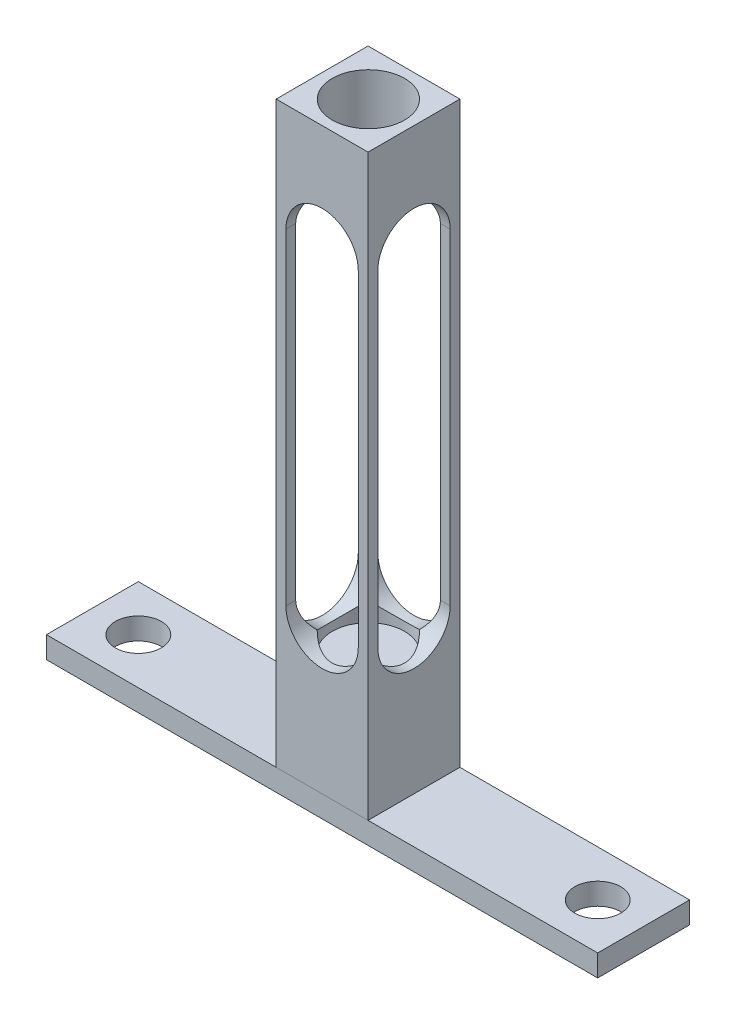
SolidWorks part; units mm, degrees
ref_plane "Front" through (0, 0, 0) normal (0, 0, 1) x (1, 0, 0)
ref_plane "Top" through (0, 0, 0) normal (0, 1, 0) x (1, 0, 0)
ref_plane "Right" through (0, 0, 0) normal (1, 0, 0) x (0, 0, -1)
other "Center of Mass"
sketch "Sketch1" plane through (0, 0, 0) normal (0, 0, 1) x (1, 0, 0)
  line L1 (0, 0) -> (12.7, 0)
  line L2 (0, 0) -> (0, 80)
  line L3 (0, 80) -> (12.7, 80)
  line L4 (12.7, 0) -> (12.7, 80)
  dimension "D1" = 80
  dimension "D2" = 12.7
extrude "Boss-Extrude1" add sketch "Sketch1" along normal blind 12.7
ref_point "Point1"
sketch "Sketch4" plane through (0, 0, 0) normal (0, -1, 0) x (-1, 0, 0)
  line L1 (31.7572, 0.0012) -> (-44.4428, 0.0012)
  line L2 (31.7572, 0.0012) -> (31.7572, -12.6988)
  line L3 (31.7572, -12.6988) -> (-44.4428, -12.6988)
  line L4 (-44.4428, 0.0012) -> (-44.4428, -12.6988)
  line L5 (31.7572, 0.0012) -> (-44.4428, -12.6988) construction
  line L6 (31.7572, -12.6988) -> (-44.4428, 0.0012) construction
  point P0 (-6.3428, -6.3488)
  dimension "D1" = 12.7
  dimension "D2" = 76.2
extrude "Boss-Extrude3" add sketch "Sketch4" along normal blind 3
sketch "Sketch12" plane through (0, 0, 12.7) normal (0, 0, 1) x (1, 0, 0)
  line L0 (6.35, 20) -> (6.35, 65.1) construction
  line L1 (1.35, 20) -> (1.35, 65.1)
  line L2 (11.35, 20) -> (11.35, 65.1)
  line L3 (44.4428, -3) -> (-31.7572, -3) construction
  line L4 (12.7, 0) -> (12.7, 80) construction
  arc A0 (1.35, 20) -> (11.35, 20) centre (6.35, 20) ccw
  arc A1 (11.35, 65.1) -> (1.35, 65.1) centre (6.35, 65.1) ccw
  point P2 (6.35, 42.55)
  dimension "D1" = 23
  dimension "D2" = 6.35
extrude "Cut-Extrude5" cut sketch "Sketch12" against normal blind 23
sketch "Sketch13" plane through (12.7, 0, 0) normal (1, 0, 0) x (0, 0, -1)
  line L0 (-6.35, 20) -> (-6.35, 65.1) construction
  line L1 (-11.35, 20) -> (-11.35, 65.1)
  line L2 (-1.35, 20) -> (-1.35, 65.1)
  line L3 (0.0012, -3) -> (-12.6988, -3) construction
  line L4 (0, 0) -> (0, 80) construction
  arc A0 (-11.35, 20) -> (-1.35, 20) centre (-6.35, 20) ccw
  arc A1 (-1.35, 65.1) -> (-11.35, 65.1) centre (-6.35, 65.1) ccw
  point P2 (-6.35, 42.55)
  point P7 (-6.3488, -3)
  dimension "D1" = 23
  dimension "D2" = 6.35
extrude "Cut-Extrude6" cut sketch "Sketch13" against normal blind 23
sketch "Sketch16" plane through (0, 80, 0) normal (0, 1, 0) x (1, 0, 0)
  circle A0 centre (6.3943, -6.3483) radius 5
extrude "Cut-Extrude8" cut sketch "Sketch16" against normal blind 66.2
sketch "Sketch17" plane through (0, 0, 0) normal (0, 1, 0) x (1, 0, 0)
  line L0 (-31.7572, 0.0012) -> (44.4428, 0.0012) construction
  line L1 (0, -12.6988) -> (-31.7572, -12.6988) construction
  circle A0 centre (-25.4072, -6.3488) radius 3.175
  point P2 (6.3428, 0.0012)
  dimension "D2" = 31.75
  dimension "D1" = 6.35
extrude "Cut-Extrude9" cut sketch "Sketch17" against normal blind 3
sketch "Sketch18" plane through (0, 0, 0) normal (0, 1, 0) x (1, 0, 0)
  line L0 (-31.7572, 0.0012) -> (44.4428, 0.0012) construction
  line L6 (12.7, -12.7) -> (0, -12.7) construction
  circle A0 centre (38.1, -6.3488) radius 3.175
  point P4 (6.35, -12.7)
  dimension "D1" = 6.35
  dimension "D2" = 31.75
extrude "Cut-Extrude10" cut sketch "Sketch18" against normal blind 3
